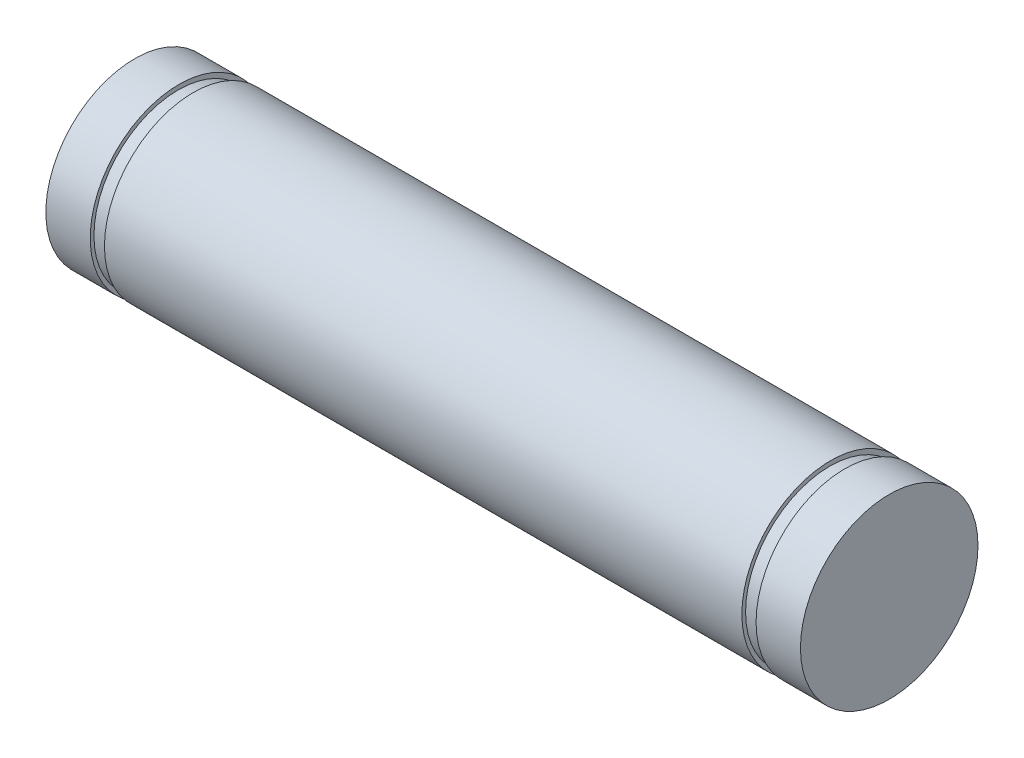
SolidWorks part; units mm, degrees
ref_plane "Front" through (0, 0, 0) normal (0, 0, 1) x (1, 0, 0)
ref_plane "Top" through (0, 0, 0) normal (0, 1, 0) x (1, 0, 0)
ref_plane "Right" through (0, 0, 0) normal (1, 0, 0) x (0, 0, -1)
sketch "Sketch1" plane through (0, 0, 0) normal (1, 0, 0) x (0, 0, -1)
  circle A0 centre (0, 0) radius 2
  dimension "D1" = 4
extrude "Boss-Extrude1" add sketch "Sketch1" along normal blind 17
ref_plane "Plane1" through (15, 0, 0) normal (0, -1, 0) x (0, 0, 1)
sketch "Sketch3" plane through (15, 0, 0) normal (0, -1, 0) x (0, 0, 1)
  line L0 (1.9165, -1) -> (2.4, -1)
  line L1 (2.4, -1) -> (2.4, -0.68)
  line L2 (2.4, -0.68) -> (1.9165, -0.68)
  line L3 (1.9165, -0.68) -> (1.9165, -1)
  line L4 (0.0165, -52.7497) -> (0.0165, 47.2503) construction
  line L5 (-2, -2) -> (2, -2) construction
  line L6 (2, 15) -> (-2, 15) construction
  line L7 (1.9165, 14) -> (3.3632, 14)
  line L8 (1.9165, 14) -> (1.9165, 13.68)
  line L9 (1.9165, 13.68) -> (3.3632, 13.68)
  line L10 (3.3632, 14) -> (3.3632, 13.68)
  dimension "D1" = 3.8
  dimension "D2" = 0.32
  dimension "D3" = 1
  dimension "D4" = 1
  dimension "D5" = 3.8
revolve "Groove for ANSI B27.7 - 3AM1-4, Basic External Retaining Ring1" cut sketch "Sketch3"
